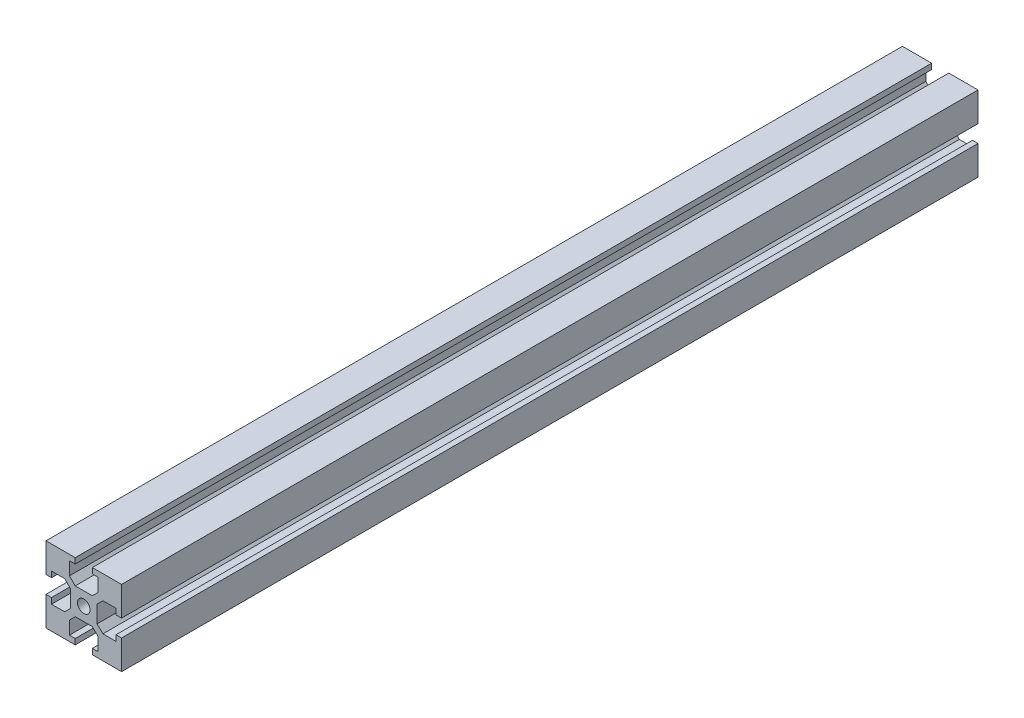
SolidWorks part; units mm, degrees
ref_plane "正面" through (0, 0, 0) normal (0, 0, 1) x (1, 0, 0)
ref_plane "平面" through (0, 0, 0) normal (0, 1, 0) x (1, 0, 0)
ref_plane "右側面" through (0, 0, 0) normal (1, 0, 0) x (0, 0, -1)
sketch "ｽｹｯﾁ2" plane through (0, 0, 0) normal (0, 0, 1) x (1, 0, 0)
  line L0 (0, 0) -> (0, 7.5) construction
  line L1 (-7.5, -7.5) -> (7.5, -7.5) construction
  line L2 (-7.5, -7.5) -> (-7.5, 7.5) construction
  line L3 (-7.5, 7.5) -> (7.5, 7.5) construction
  line L4 (7.5, -7.5) -> (7.5, 7.5) construction
  line L5 (-7.5, -7.5) -> (7.5, 7.5) construction
  line L6 (-7.5, 7.5) -> (7.5, -7.5) construction
  line L8 (1.7, 2.65) -> (-1.7, 2.65)
  line L9 (-2.85, 3.8) -> (2.85, 3.8) construction
  line L10 (-2.85, 6.4) -> (-2.85, 3.8)
  line L11 (2.85, 6.4) -> (2.85, 3.8)
  line L12 (-2.85, 3.8) -> (-1.7, 2.65)
  line L13 (1.7, 2.65) -> (2.85, 3.8)
  line L14 (-2.85, 6.4) -> (-1.7, 6.4)
  line L15 (-1.7, 6.4) -> (-1.7, 7.5)
  line L16 (-1.7, 7.5) -> (-7.5, 7.5)
  line L17 (2.85, 6.4) -> (1.7, 6.4)
  line L18 (1.7, 6.4) -> (1.7, 7.5)
  line L19 (1.7, 7.5) -> (7.5, 7.5)
  line L20 (3.8, 2.85) -> (2.65, 1.7)
  line L21 (2.65, -1.7) -> (2.65, 1.7)
  line L22 (2.65, -1.7) -> (3.8, -2.85)
  line L23 (6.4, -2.85) -> (6.4, -1.7)
  line L24 (6.4, -2.85) -> (3.8, -2.85)
  line L25 (6.4, -1.7) -> (7.5, -1.7)
  line L26 (7.5, -1.7) -> (7.5, -7.5)
  line L27 (6.4, 1.7) -> (7.5, 1.7)
  line L28 (7.5, 1.7) -> (7.5, 7.5)
  line L29 (6.4, 2.85) -> (6.4, 1.7)
  line L30 (6.4, 2.85) -> (3.8, 2.85)
  line L31 (2.85, -3.8) -> (1.7, -2.65)
  line L32 (-1.7, -2.65) -> (1.7, -2.65)
  line L33 (-1.7, -2.65) -> (-2.85, -3.8)
  line L34 (-2.85, -6.4) -> (-1.7, -6.4)
  line L35 (-2.85, -6.4) -> (-2.85, -3.8)
  line L36 (-1.7, -6.4) -> (-1.7, -7.5)
  line L37 (-1.7, -7.5) -> (-7.5, -7.5)
  line L38 (1.7, -6.4) -> (1.7, -7.5)
  line L39 (1.7, -7.5) -> (7.5, -7.5)
  line L40 (2.85, -6.4) -> (1.7, -6.4)
  line L41 (2.85, -6.4) -> (2.85, -3.8)
  line L42 (-3.8, -2.85) -> (-2.65, -1.7)
  line L43 (-2.65, 1.7) -> (-2.65, -1.7)
  line L44 (-2.65, 1.7) -> (-3.8, 2.85)
  line L45 (-6.4, 2.85) -> (-6.4, 1.7)
  line L46 (-6.4, 2.85) -> (-3.8, 2.85)
  line L47 (-6.4, 1.7) -> (-7.5, 1.7)
  line L48 (-7.5, 1.7) -> (-7.5, 7.5)
  line L49 (-6.4, -1.7) -> (-7.5, -1.7)
  line L50 (-7.5, -1.7) -> (-7.5, -7.5)
  line L51 (-6.4, -2.85) -> (-6.4, -1.7)
  line L52 (-6.4, -2.85) -> (-3.8, -2.85)
  circle A0 centre (0, 0) radius 1.25
  point P0 (0, 0)
  point P11 (0, 7.5)
  point P14 (0, 2.65)
  point P17 (0, 3.8)
  dimension "D8" = 2.5
  dimension "D1" = 15
  dimension "D2" = 3.4
  dimension "D3" = 1.1
  dimension "D4" = 2.6
  dimension "D5" = 5.7
  dimension "D6" = 3.4
  dimension "D7" = 4
extrude "ﾎﾞｽ - 押し出し1" add sketch "ｽｹｯﾁ2" along normal blind 170
